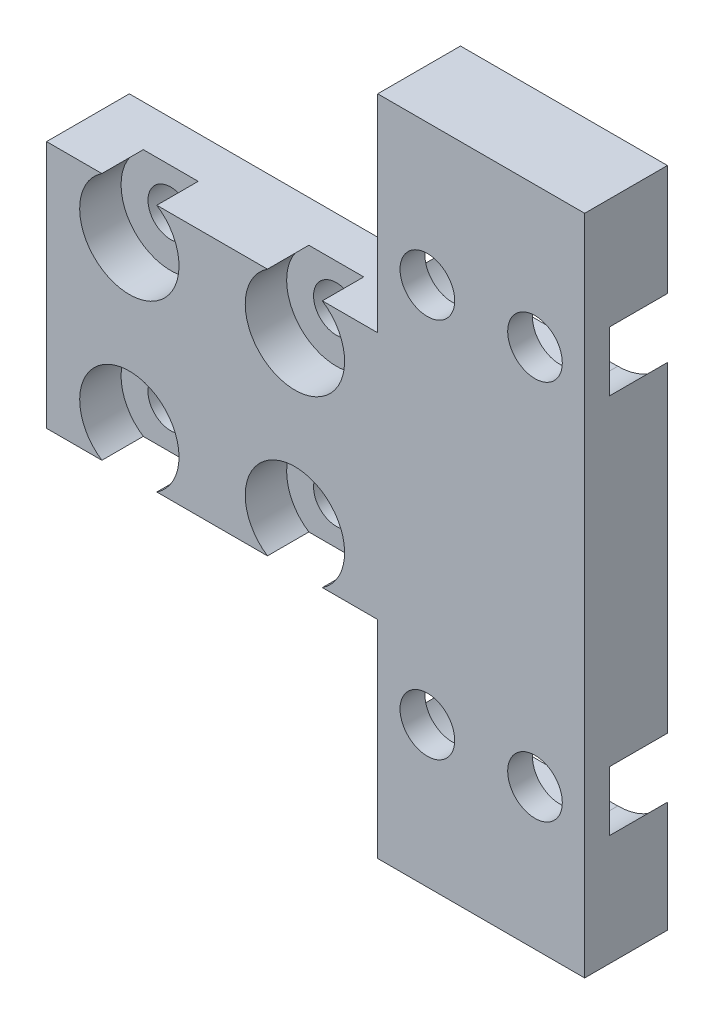
SolidWorks part; units mm, degrees
ref_plane "Plan de face" through (0, 0, 0) normal (0, 0, 1) x (1, 0, 0)
ref_plane "Plan de dessus" through (0, 0, 0) normal (0, 1, 0) x (1, 0, 0)
ref_plane "Plan de droite" through (0, 0, 0) normal (1, 0, 0) x (0, 0, -1)
sketch "Esquisse1" plane through (0, 0, 0) normal (0, 0, 1) x (1, 0, 0)
  line L0 (0.8219, 26.0384) -> (0.8219, -19.9616) construction
  line L4 (6.8219, 43.0384) -> (6.8219, -36.9616)
  line L5 (6.8219, 43.0384) -> (-18.1781, 43.0384)
  line L6 (-18.1781, 43.0384) -> (-18.1781, 18.0384)
  line L7 (-18.1781, 18.0384) -> (-58.1781, 18.0384)
  line L8 (-58.1781, 18.0384) -> (-58.1781, -11.9616)
  line L9 (-58.1781, -11.9616) -> (-18.1781, -11.9616)
  line L10 (-18.1781, -11.9616) -> (-18.1781, -36.9616)
  line L11 (-18.1781, -36.9616) -> (6.8219, -36.9616)
  line L12 (-48.1781, 13.0384) -> (-48.1781, -6.9616) construction
  circle A0 centre (0.8219, 26.0384) radius 3.3
  circle A1 centre (-12.1781, 26.0384) radius 3.3
  circle A2 centre (-12.1781, -19.9616) radius 3.3
  circle A3 centre (0.8219, -19.9616) radius 3.3
  circle A4 centre (-48.1781, 13.0384) radius 2.75
  circle A5 centre (-28.1781, 13.0384) radius 2.75
  circle A6 centre (-28.1781, -6.9616) radius 2.75
  circle A7 centre (-48.1781, -6.9616) radius 2.75
  point P12 (0.8219, 3.0384)
  point P13 (6.8219, 3.0384)
  point P23 (-48.1781, 3.0384)
  point P27 (-58.1781, 3.0384)
  dimension "D1" = 6.6
  dimension "D7" = 5.5
  dimension "D2" = 6
  dimension "D3" = 13
  dimension "D4" = 46
  dimension "D5" = 80
  dimension "D6" = 25
  dimension "D8" = 40
  dimension "D9" = 30
  dimension "D10" = 20
  dimension "D11" = 20
  dimension "D12" = 10
extrude "Boss.-Extru.1" add sketch "Esquisse1" along normal blind 10
sketch "Esquisse2" plane through (0, 0, 10) normal (0, 0, 1) x (1, 0, 0)
  circle A0 centre (-48.1781, 13.0384) radius 6
  circle A1 centre (-28.1781, 13.0384) radius 6
  circle A2 centre (-28.1781, -6.9616) radius 6
  circle A3 centre (-48.1781, -6.9616) radius 6
  dimension "D1" = 12
extrude "Enlèv. mat.-Extru.1" cut sketch "Esquisse2" against normal blind 5
sketch "Esquisse3" plane through (0, 0, 0) normal (0, 0, -1) x (-1, 0, 0)
  line L0 (-0.8219, 33.0384) -> (12.1781, 33.0384)
  line L1 (-0.8219, 19.0384) -> (12.1781, 19.0384)
  line L2 (-0.8219, -19.9616) -> (12.1781, -19.9616) construction
  line L3 (-0.8219, -12.9616) -> (12.1781, -12.9616)
  line L4 (-0.8219, -26.9616) -> (12.1781, -26.9616)
  arc A4 (-0.8219, 33.0384) -> (-0.8219, 19.0384) centre (-0.8219, 26.0384) ccw
  arc A5 (12.1781, 33.0384) -> (12.1781, 19.0384) centre (12.1781, 26.0384) cw
  arc A6 (-0.8219, -12.9616) -> (-0.8219, -26.9616) centre (-0.8219, -19.9616) ccw
  arc A7 (12.1781, -26.9616) -> (12.1781, -12.9616) centre (12.1781, -19.9616) ccw
  point P6 (5.6781, -19.9616)
  dimension "D1" = 7
  dimension "D2" = 7
extrude "Enlèv. mat.-Extru.3" cut sketch "Esquisse3" against normal blind 7
